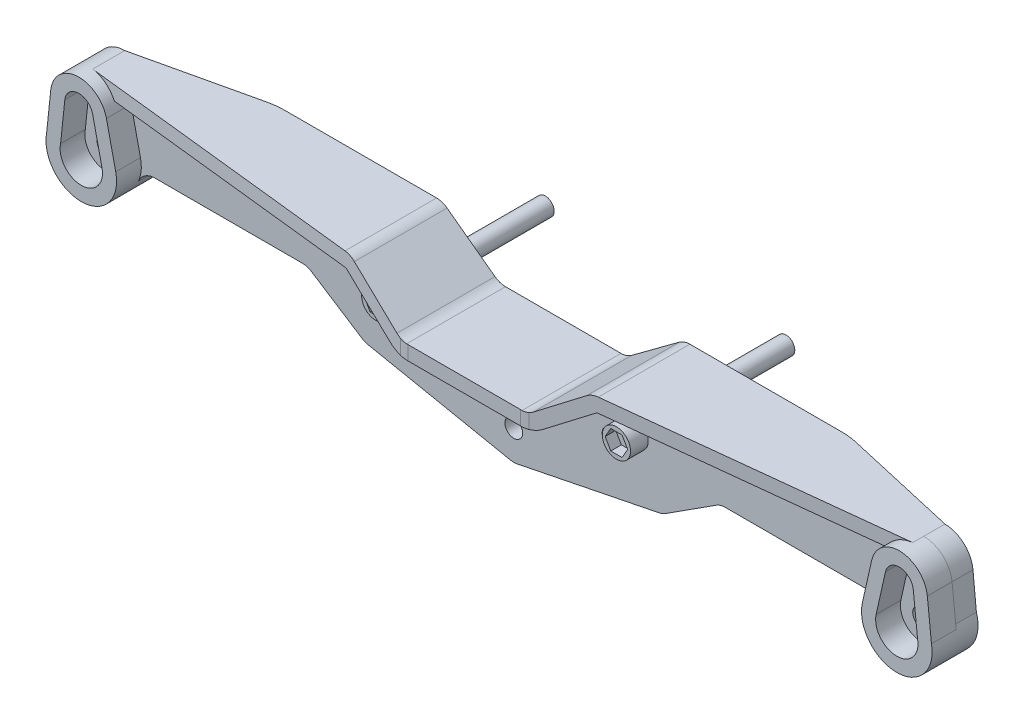
SolidWorks part; units mm, degrees
ref_plane "Front Plane" through (0, 0, 0) normal (0, 0, 1) x (1, 0, 0)
ref_plane "Top Plane" through (0, 0, 0) normal (0, 1, 0) x (1, 0, 0)
ref_plane "Right Plane" through (0, 0, 0) normal (1, 0, 0) x (0, 0, -1)
sketch "Sketch3" plane through (0, 0, 0) normal (0, 0, 1) x (1, 0, 0)
  line L0 (-58.0676, 9.1299) -> (-17.9277, 9.1299)
  line L1 (-16.4399, 8.639) -> (-9.6629, 3.6207)
  line L2 (-62.0442, 5.5617) -> (-62.6952, -0.4332)
  line L3 (20.6174, -6.7133) -> (0.4941, -10.7705)
  line L4 (28.6186, -1.7679) -> (21.4763, -6.3649)
  line L5 (-50.8066, -1.3701) -> (-29.9716, -1.3701)
  line L6 (-28.6186, -1.7679) -> (-21.4763, -6.3649)
  line L7 (-20.6174, -6.7133) -> (-0.4941, -10.7705)
  line L8 (-8.1752, 3.1299) -> (8.1752, 3.1299)
  line L9 (50.8066, -1.3701) -> (29.9716, -1.3701)
  line L10 (62.0062, 5.5147) -> (62.4857, 0.5536)
  line L11 (16.4399, 8.639) -> (9.6629, 3.6207)
  line L12 (0, 3.1299) -> (0, -6.6201) construction
  line L13 (-20.3031, 3.614) -> (-13.7583, -0.973) construction
  line L14 (0, -5.3701) -> (5.8477, -5.3701) construction
  line L15 (58.0247, 9.1299) -> (17.9277, 9.1299)
  circle A0 centre (0, -6.6201) radius 1.25
  circle A1 centre (-57.7244, -0.973) radius 1.25
  arc A2 (-62.6952, -0.4332) -> (-53.1125, -2.9044) centre (-57.7244, -0.973) ccw
  arc A3 (62.4857, 0.5536) -> (53.1125, -2.9044) centre (57.7244, -0.973) cw
  circle A4 centre (57.7244, -0.973) radius 1.25
  circle A5 centre (-20.3031, 3.614) radius 1.25
  circle A6 centre (-17.0307, 1.3205) radius 1.25
  circle A7 centre (-13.7583, -0.973) radius 1.25
  circle A8 centre (13.7583, -0.973) radius 1.25
  circle A9 centre (17.0307, 1.3205) radius 1.25
  circle A10 centre (20.3031, 3.614) radius 1.25
  arc A11 (62.0062, 5.5147) -> (58.0247, 9.1299) centre (58.0247, 5.1299) ccw
  arc A12 (-58.0676, 9.1299) -> (-62.0442, 5.5617) centre (-58.0676, 5.1299) ccw
  arc A13 (-9.6629, 3.6207) -> (-8.1752, 3.1299) centre (-8.1752, 5.6299) ccw
  arc A14 (8.1752, 3.1299) -> (9.6629, 3.6207) centre (8.1752, 5.6299) ccw
  arc A15 (17.9277, 9.1299) -> (16.4399, 8.639) centre (17.9277, 6.6299) ccw
  arc A16 (-17.9277, 9.1299) -> (-16.4399, 8.639) centre (-17.9277, 6.6299) cw
  arc A17 (29.9716, -1.3701) -> (28.6186, -1.7679) centre (29.9716, -3.8701) ccw
  arc A18 (21.4763, -6.3649) -> (20.6174, -6.7133) centre (20.1233, -4.2627) cw
  arc A19 (0.4941, -10.7705) -> (-0.4941, -10.7705) centre (0, -8.3198) cw
  arc A20 (-20.6174, -6.7133) -> (-21.4763, -6.3649) centre (-20.1233, -4.2627) cw
  arc A21 (-28.6186, -1.7679) -> (-29.9716, -1.3701) centre (-29.9716, -3.8701) ccw
  arc A22 (53.1125, -2.9044) -> (50.8066, -1.3701) centre (50.8066, -3.8701) ccw
  arc A23 (-50.8066, -1.3701) -> (-53.1125, -2.9044) centre (-50.8066, -3.8701) ccw
  point P29 (61.6568, 9.1299)
  point P33 (-61.6568, 9.1299)
  point P34 (2.9239, -5.3701)
  point P44 (-9, 3.1299)
  point P49 (9, 3.1299)
  point P52 (17.1028, 9.1299)
  point P56 (-17.1028, 9.1299)
  point P59 (29.2366, -1.3701)
  point P62 (21.0797, -6.6201)
  point P65 (0, -10.8701)
  point P68 (-21.0797, -6.6201)
  point P71 (-29.2366, -1.3701)
  point P74 (52.7402, -1.3701)
  point P77 (-52.7402, -1.3701)
  dimension "D5" = 2.5
  dimension "D2" = 2.5
  dimension "D8" = 5
  dimension "D14" = 2.5
  dimension "D15" = 2.5
  dimension "D16" = 2.5
  dimension "D17" = 4
  dimension "D18" = 2.5
  dimension "D3" = 18
  dimension "D4" = 6
  dimension "D6" = 8.5
  dimension "D7" = 58
  dimension "D9" = 3.1798
  dimension "D10" = 6.6201
  dimension "D11" = 14
  dimension "D12" = 10.5
  dimension "D13" = 96.197
extrude "Boss-Extrude2" add sketch "Sketch3" along normal blind 3 separate body contours L0 A16 L1 A13 L8 A14 L11 A15 L15 A11 L10 A3 A22 L9 A17 L4 A18 L3 A19 L7 A20 L6 A21 L5 A23 A2 L2 A12
sketch "Sketch5" plane through (0, 0, 3) normal (0, 0, 1) x (1, 0, 0)
  line L25 (58.0247, 7.1299) -> (17.9277, 7.1299)
  line L26 (17.6301, 7.0317) -> (10.8531, 2.0134)
  line L27 (8.1752, 1.1299) -> (-8.1752, 1.1299)
  line L28 (-10.8531, 2.0134) -> (-17.6301, 7.0317)
  line L29 (-17.9277, 7.1299) -> (-58.0676, 7.1299)
  line L30 (58.0247, 9.1299) -> (17.9277, 9.1299)
  line L31 (16.4399, 8.639) -> (9.6629, 3.6207)
  line L32 (8.1752, 3.1299) -> (-8.1752, 3.1299)
  line L33 (-9.6629, 3.6207) -> (-16.4399, 8.639)
  line L34 (-17.9277, 9.1299) -> (-58.0676, 9.1299)
  line L35 (58.0247, 9.1299) -> (17.9277, 9.1299)
  line L36 (16.4399, 8.639) -> (9.6629, 3.6207)
  line L37 (8.1752, 3.1299) -> (-8.1752, 3.1299)
  line L38 (-9.6629, 3.6207) -> (-16.4399, 8.639)
  line L39 (-17.9277, 9.1299) -> (-58.0676, 9.1299)
  line L40 (-58.0676, 9.1299) -> (-58.0676, 7.1299)
  line L41 (-58.0676, 7.1299) -> (-58.2669, 6.7547)
  line L42 (58.0247, 9.1299) -> (58.0247, 7.1299)
  arc A20 (17.9277, 7.1299) -> (17.6301, 7.0317) centre (17.9277, 6.6299) ccw
  arc A21 (8.1752, 1.1299) -> (10.8531, 2.0134) centre (8.1752, 5.6299) ccw
  arc A22 (-10.8531, 2.0134) -> (-8.1752, 1.1299) centre (-8.1752, 5.6299) ccw
  arc A23 (-17.6301, 7.0317) -> (-17.9277, 7.1299) centre (-17.9277, 6.6299) ccw
  arc A24 (17.9277, 9.1299) -> (16.4399, 8.639) centre (17.9277, 6.6299) ccw
  arc A25 (8.1752, 3.1299) -> (9.6629, 3.6207) centre (8.1752, 5.6299) ccw
  arc A26 (-9.6629, 3.6207) -> (-8.1752, 3.1299) centre (-8.1752, 5.6299) ccw
  arc A27 (-16.4399, 8.639) -> (-17.9277, 9.1299) centre (-17.9277, 6.6299) ccw
  arc A28 (17.9277, 9.1299) -> (16.4399, 8.639) centre (17.9277, 6.6299) ccw
  arc A29 (8.1752, 3.1299) -> (9.6629, 3.6207) centre (8.1752, 5.6299) ccw
  arc A30 (-9.6629, 3.6207) -> (-8.1752, 3.1299) centre (-8.1752, 5.6299) ccw
  arc A31 (-16.4399, 8.639) -> (-17.9277, 9.1299) centre (-17.9277, 6.6299) ccw
  line M15 (58.0247, 9.1299) -> (17.9277, 9.1299)
  arc M16 (17.9277, 9.1299) -> (16.4399, 8.639) centre (17.9277, 6.6299) ccw
  line M17 (16.4399, 8.639) -> (9.6629, 3.6207)
  arc M18 (9.6629, 3.6207) -> (8.1752, 3.1299) centre (8.1752, 5.6299) cw
  line M19 (8.1752, 3.1299) -> (-8.1752, 3.1299)
  arc M20 (-8.1752, 3.1299) -> (-9.6629, 3.6207) centre (-8.1752, 5.6299) cw
  line M21 (-9.6629, 3.6207) -> (-16.4399, 8.639)
  arc M22 (-16.4399, 8.639) -> (-17.9277, 9.1299) centre (-17.9277, 6.6299) ccw
  line M23 (-17.9277, 9.1299) -> (-58.0676, 9.1299)
  dimension "D1" = 0
  dimension "D2" = 2
extrude "Boss-Extrude3" add sketch "Sketch5" along normal blind 7 and the other way blind 7 contours A23 L28 A22 L27 A21 L26 A20 L25 L42 L40 L29 M15 M16 M17 M18 M19 M20 M21 M22 M23
sketch "Sketch6" plane through (0, 9.1299, 0) normal (0, 1, 0) x (1, 0, 0)
  line L0 (-58.0676, 0) -> (-41.6675, 3.7486)
  line L1 (-17.9277, 4) -> (-58.0676, 4) construction
  line L2 (-39.4393, 4) -> (0, 4)
  line L3 (8.1752, 4) -> (-8.1752, 4) construction
  line L4 (-40.5676, 4) -> (-31.0563, 4)
  line L5 (-39.4393, 4) -> (-58.0676, 4)
  line L6 (-58.0676, 4) -> (-58.0676, 0)
  line L7 (-58.0676, -4.5466) -> (-9.0763, -9.9399)
  line L8 (-58.0676, -3) -> (-58.0676, -10) construction
  line L9 (-9.6629, -10) -> (-8.1752, -10) construction
  line L10 (-7.9821, -10) -> (-5.3351, -10)
  line L11 (8.1752, -10) -> (-8.1752, -10) construction
  line L12 (-58.0676, -10) -> (-58.0676, -4.5466)
  line L13 (0, 0) -> (0, -5.2785) construction
  line L14 (58.0676, -10) -> (58.0676, -4.5466)
  line L15 (7.9821, -10) -> (5.3351, -10)
  line L16 (58.0676, -4.5466) -> (9.0763, -9.9399)
  line L17 (58.0676, 4) -> (58.0676, 0)
  line L18 (39.4393, 4) -> (58.0676, 4)
  line L19 (40.5676, 4) -> (31.0563, 4)
  line L20 (58.0676, 0) -> (41.6675, 3.7486)
  line L21 (-58.0676, -10) -> (-7.9821, -10)
  line L22 (7.9821, -10) -> (58.0676, -10)
  arc A0 (-41.6675, 3.7486) -> (-39.4393, 4) centre (-39.4393, -6) cw
  arc A1 (-7.9821, -10) -> (-9.0763, -9.9399) centre (-7.9821, 0) cw
  arc A2 (7.9821, -10) -> (9.0763, -9.9399) centre (7.9821, 0) ccw
  arc A3 (41.6675, 3.7486) -> (39.4393, 4) centre (39.4393, -6) ccw
  point P25 (-8.5308, -10)
  point P44 (8.5308, -10)
  line M3 (-17.9277, -10) -> (-17.9277, 4)
  line M4 (-17.9277, 4) -> (-58.0676, 4)
  line M5 (-58.0676, 4) -> (-58.0676, 0)
  line M7 (-58.0676, -3) -> (-58.0676, -10)
  line M8 (-58.0676, -10) -> (-17.9277, -10)
  dimension "D2" = 10
  dimension "D3" = 10
  dimension "D1" = 17.5
extrude "Cut-Extrude1" cut sketch "Sketch6" against normal through all contours L0 A0 M4 M5 | L7 M7 M8 M3 | A3 L20 L17 L18 | A2 L22 L14 L16
sketch "Sketch7" plane through (0, 0, 3) normal (0, 0, 1) x (1, 0, 0)
  line L0 (-62.6288, 0) -> (-62.0442, 5.5617)
  line L1 (-54.1645, 6.0048) -> (-52.8455, 0.1207)
  line L2 (-56.116, 5.5673) -> (-54.7971, -0.3168)
  line L3 (-60.6506, -0.3113) -> (-60.0556, 5.3486)
  arc A0 (-62.6288, 0) -> (-52.8455, 0.1207) centre (-57.7244, -0.973) ccw
  arc A1 (-62.6952, -0.4332) -> (-53.1125, -2.9044) centre (-57.7244, -0.973) ccw construction
  arc A2 (-62.0442, 5.5617) -> (-54.1645, 6.0048) centre (-58.0676, 5.1299) cw
  arc A3 (-58.0676, 9.1299) -> (-62.0442, 5.5617) centre (-58.0676, 5.1299) ccw construction
  arc A4 (-60.0556, 5.3486) -> (-56.116, 5.5673) centre (-58.0676, 5.1299) cw
  arc A5 (-60.6506, -0.3113) -> (-54.7971, -0.3168) centre (-57.7244, -0.973) ccw
  dimension "D1" = 2
extrude "Boss-Extrude4" add sketch "Sketch7" along normal blind 3.5
mirror "Mirror1" about plane through (0, 0, 0) normal (1, 0, 0) of "Boss-Extrude4"
sketch "Sketch8" plane through (0, 0, -4) normal (0, 0, -1) x (-1, 0, 0)
  line L0 (-23.819, 3.614) -> (-24.839, 3.614)
  line L1 (-24.839, 3.614) -> (-24.839, 7.1299)
  line L2 (-58.0247, 7.1299) -> (-17.9277, 7.1299) construction
  line L3 (-24.839, 7.1299) -> (-20.3031, 7.1299)
  line L4 (0, 0) -> (0, -2.7665) construction
  line L5 (24.839, 7.1299) -> (20.3031, 7.1299)
  line L6 (24.839, 3.614) -> (24.839, 7.1299)
  line L7 (23.819, 3.614) -> (24.839, 3.614)
  arc A0 (-20.3031, 7.1299) -> (-23.819, 3.614) centre (-20.3031, 3.614) ccw
  arc A1 (20.3031, 7.1299) -> (23.819, 3.614) centre (20.3031, 3.614) cw
extrude "Boss-Extrude5" add sketch "Sketch8" against normal up to surface (4 mm away) up to face at (56.4744, -0.973, 0)
sketch "Sketch9" plane through (0, 0, 3) normal (0, 0, 1) x (1, 0, 0)
  circle A0 centre (17.0307, 1.3205) radius 2
  dimension "D1" = 4
extrude "Boss-Extrude6" add sketch "Sketch9" along normal blind 2.5
sketch "Sketch10" plane through (0, 0, 5.5) normal (0, 0, 1) x (1, 0, 0)
  circle A0 centre (17.0307, 1.3205) radius 1.25
  circle A1 centre (17.0307, 1.3205) radius 2 construction
  dimension "D1" = 2.5
extrude "Boss-Extrude7" add sketch "Sketch10" against normal blind 24
sketch "Sketch11" plane through (0, 0, 5.5) normal (0, 0, 1) x (1, 0, 0)
  line L1 (17.8274, 2.7004) -> (16.234, 2.7004)
  line L2 (16.234, 2.7004) -> (15.4373, 1.3205)
  line L3 (15.4373, 1.3205) -> (16.234, -0.0594)
  line L4 (16.234, -0.0594) -> (17.8274, -0.0594)
  line L5 (17.8274, -0.0594) -> (18.6241, 1.3205)
  line L6 (18.6241, 1.3205) -> (17.8274, 2.7004)
  circle A0 centre (17.0307, 1.3205) radius 1.3799 construction
extrude "Cut-Extrude2" cut sketch "Sketch11" against normal blind 1.5
sketch "Sketch12" plane through (0, 0, 0) normal (0, 0, -1) x (-1, 0, 0)
  line L1 (-15.2986, 4.3205) -> (-18.7627, 4.3205)
  line L2 (-18.7627, 4.3205) -> (-20.4948, 1.3205)
  line L3 (-20.4948, 1.3205) -> (-18.7627, -1.6795)
  line L4 (-18.7627, -1.6795) -> (-15.2986, -1.6795)
  line L5 (-15.2986, -1.6795) -> (-13.5666, 1.3205)
  line L6 (-13.5666, 1.3205) -> (-15.2986, 4.3205)
  circle A0 centre (-17.0307, 1.3205) radius 1.25
  circle A1 centre (-17.0307, 1.3205) radius 1.25 construction
  circle A2 centre (-17.0307, 1.3205) radius 3 construction
  dimension "D1" = 6
extrude "Boss-Extrude8" add sketch "Sketch12" along normal blind 2.5
mirror "Mirror2" about plane through (0, 0, 0) normal (1, 0, 0) of "Boss-Extrude8", "Cut-Extrude2", "Boss-Extrude7", "Boss-Extrude6"
